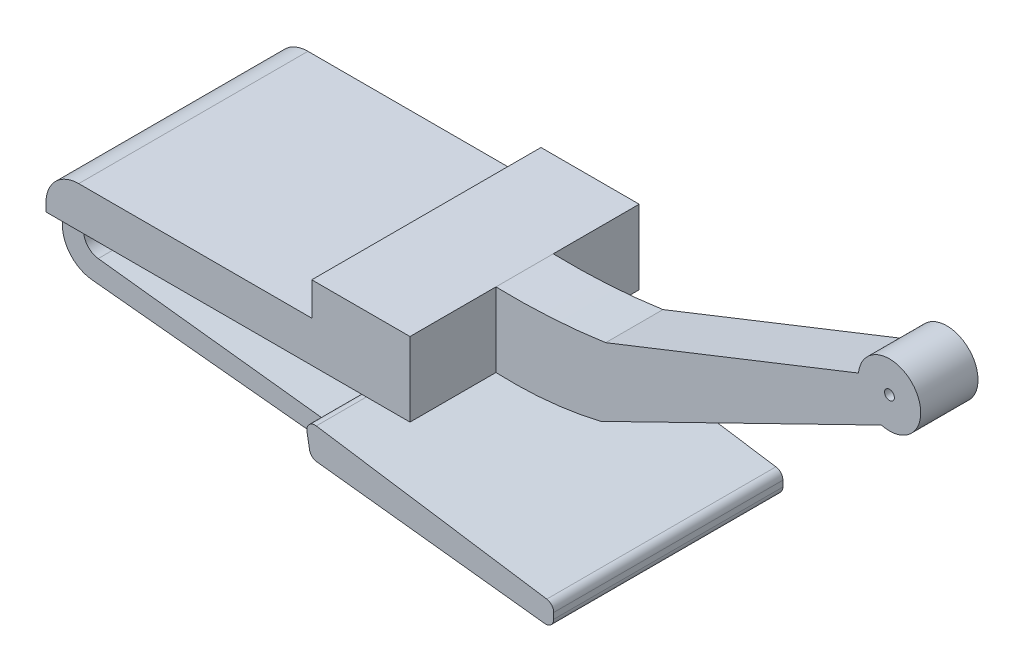
SolidWorks part; units mm, degrees
ref_plane "Front Plane" through (0, 0, 0) normal (0, 0, 1) x (1, 0, 0)
ref_plane "Top Plane" through (0, 0, 0) normal (0, 1, 0) x (1, 0, 0)
ref_plane "Right Plane" through (0, 0, 0) normal (1, 0, 0) x (0, 0, -1)
sketch "Sketch1" plane through (0, 0, 0) normal (0, 0, 1) x (1, 0, 0)
  line L0 (9.1765, 3.8529) -> (9.1765, 8.3824)
  line L1 (9.1765, 8.3824) -> (3.1765, 8.3824)
  line L2 (3.1765, 8.3824) -> (3.1765, 6.3529)
  line L3 (3.1765, 6.3529) -> (-11.0588, 6.3529)
  line L4 (-13.0588, 4.3529) -> (-13.0588, 3.8529)
  line L5 (-13.0588, 3.8529) -> (9.1765, 3.8529)
  arc A0 (-13.0588, 4.3529) -> (-11.0588, 6.3529) centre (-11.0588, 4.3529) cw
  point P8 (-13.0588, 6.3529)
  dimension "D3" = 2
  dimension "D1" = 6
  dimension "D2" = 2.5
extrude "Boss-Extrude1" add sketch "Sketch1" along normal mid plane 14
sketch "Sketch2" plane through (0, 0, 0) normal (0, 0, 1) x (1, 0, 0)
  line L0 (-13.0588, 3.8529) -> (-13.0588, 2.6605)
  line L1 (-11.2605, 0.6707) -> (3.0728, -0.7823)
  line L2 (3.0728, -0.7823) -> (3.0728, 0.3576)
  line L3 (3.0728, 0.3576) -> (-10.8683, 1.9823)
  line L4 (-11.7526, 2.9755) -> (-11.7526, 3.8529)
  line L5 (-13.0588, 3.8529) -> (9.1765, 3.8529) construction
  line L6 (-13.0588, 3.8529) -> (-11.7526, 3.8529)
  arc A0 (-11.2605, 0.6707) -> (-13.0588, 2.6605) centre (-11.0588, 2.6605) cw
  arc A1 (-10.8683, 1.9823) -> (-11.7526, 2.9755) centre (-10.7526, 2.9755) cw
  point P11 (-13.0588, 0.8529)
  dimension "D2" = 2
  dimension "D3" = 1
  dimension "D1" = 3
extrude "Boss-Extrude2" add sketch "Sketch2" along normal mid plane 12
sketch "Sketch3" plane through (0, 0, 0) normal (0, 0, 1) x (1, 0, 0)
  line L0 (2.8831, 0.2056) -> (3.0421, -0.6843)
  line L1 (3.4774, -1.0932) -> (17.3979, -2.6869)
  line L2 (17.9548, -2.1902) -> (17.9548, -1.8281)
  line L3 (17.5293, -1.3336) -> (3.4498, 0.7879)
  arc A0 (3.0421, -0.6843) -> (3.4774, -1.0932) centre (3.5343, -0.5964) ccw
  arc A1 (17.3979, -2.6869) -> (17.9548, -2.1902) centre (17.4548, -2.1902) ccw
  arc A2 (17.9548, -1.8281) -> (17.5293, -1.3336) centre (17.4548, -1.8281) ccw
  arc A3 (2.8831, 0.2056) -> (3.4498, 0.7879) centre (3.3753, 0.2935) cw
  dimension "D1" = 0.5
extrude "Boss-Extrude3" add sketch "Sketch3" along normal mid plane 14
sketch "Sketch4" plane through (0, 0, 0) normal (0, 0, 1) x (1, 0, 0)
  line L0 (15.8805, 8.784) -> (31.3183, 14.8946)
  line L1 (15.583, 4.4724) -> (32.7227, 12.8437)
  line L2 (9.1765, 8.3824) -> (9.1765, 3.8529)
  arc A0 (31.3183, 14.8946) -> (32.7227, 12.8437) centre (33.2164, 14.688) cw
  circle A1 centre (33.2164, 14.688) radius 0.3
  spline S0 degree 2 poles (9.1765, 8.3824) (12.5408, 8.2959) (15.8805, 8.784) knots 0 0 0 1 1 1
  spline S1 degree 2 poles (9.1765, 3.8529) (12.4115, 3.7115) (15.583, 4.4724) knots 0 0 0 1 1 1
extrude "Boss-Extrude4" add sketch "Sketch4" along normal mid plane 3.5
